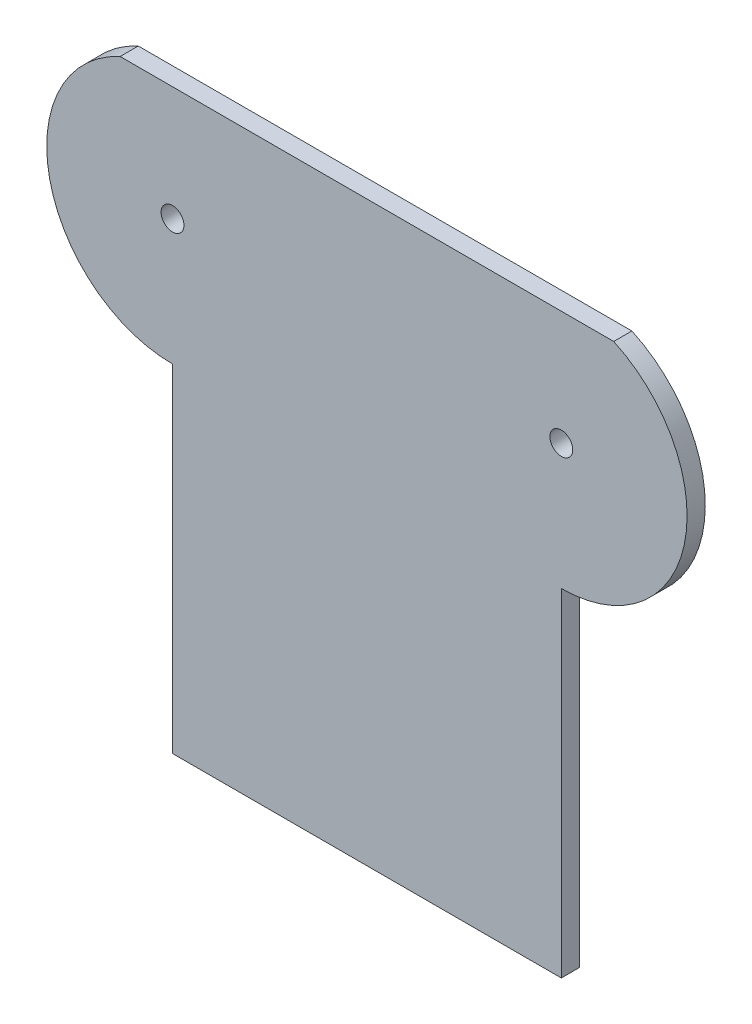
SolidWorks part; units mm, degrees
ref_plane "Front Plane" through (0, 0, 0) normal (0, 0, 1) x (1, 0, 0)
ref_plane "Top Plane" through (0, 0, 0) normal (0, 1, 0) x (1, 0, 0)
ref_plane "Right Plane" through (0, 0, 0) normal (1, 0, 0) x (0, 0, -1)
sketch "Sketch1" plane through (0, 0, 0) normal (0, 0, 1) x (1, 0, 0)
  line L0 (90, 70) -> (90, 0) construction
  line L2 (0, 0) -> (0, 70) construction
  line L3 (46.8348, 70) -> (133.1652, 70)
  line L4 (180, 0) -> (180, 70) construction
  line L5 (56, 28) -> (56, 0)
  line L6 (124, 28) -> (124, 0)
  line L7 (0, 70) -> (46.8348, 70) construction
  line L8 (133.1652, 70) -> (180, 70) construction
  line L9 (0, 0) -> (56, 0) construction
  line L10 (124, 0) -> (180, 0) construction
  line L11 (56, 0) -> (124, 0) construction
  line L12 (56, 0) -> (56, -31)
  line L13 (56, -31) -> (124, -31)
  line L14 (124, -31) -> (124, 0)
  circle A0 centre (56, 50) radius 2
  circle A1 centre (124, 50) radius 2
  arc A2 (46.8348, 70) -> (56, 28) centre (56, 50) ccw
  arc A3 (133.1652, 70) -> (124, 28) centre (124, 50) cw
  dimension "D3" = 4
  dimension "D7" = 46.8348
  dimension "D8" = 22
  dimension "D1" = 70
  dimension "D2" = 180
  dimension "D4" = 68
  dimension "D5" = 34
  dimension "D6" = 31
  dimension "D9" = 56
extrude "Boss-Extrude1" add sketch "Sketch1" along normal blind 3.175
